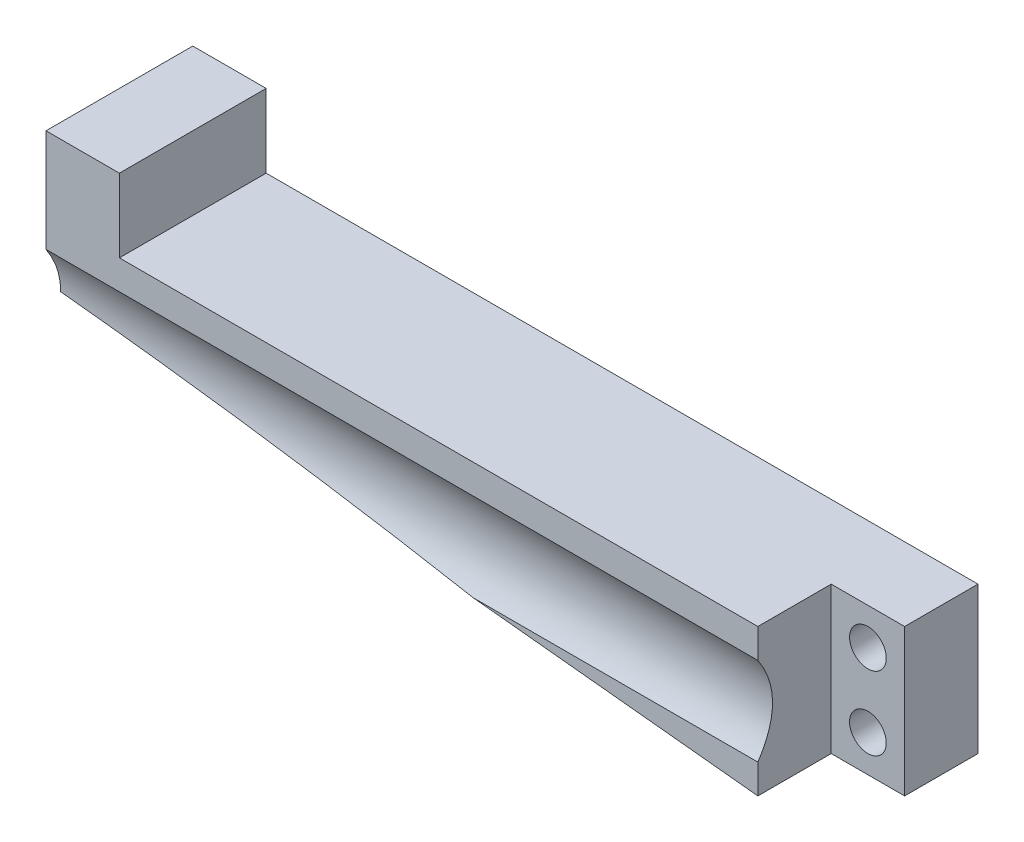
SolidWorks part; units mm, degrees
ref_plane "Plan de face" through (0, 0, 0) normal (0, 0, 1) x (1, 0, 0)
ref_plane "Plan de dessus" through (0, 0, 0) normal (0, 1, 0) x (1, 0, 0)
ref_plane "Plan de droite" through (0, 0, 0) normal (1, 0, 0) x (0, 0, -1)
sketch "Esquisse1" plane through (0, 0, 0) normal (0, 0, 1) x (1, 0, 0)
  line L0 (-102, 0) -> (-5, -10)
  line L1 (-5, -10) -> (5, -10)
  line L3 (-5, 10) -> (5, 10)
  line L4 (5, -10) -> (5, 10)
  line L5 (-5, -10) -> (5, 10) construction
  line L6 (-5, 10) -> (5, -10) construction
  line L7 (-5, 10) -> (-92, 10)
  line L10 (-102, 10) -> (-102, 0)
  line L12 (-102, 10) -> (-102, 20)
  line L13 (-102, 20) -> (-92, 20)
  line L14 (-92, 10) -> (-92, 20)
  circle A0 centre (0, 5) radius 2.5
  circle A1 centre (0, -5) radius 2.5
  point P0 (0, 0)
  dimension "D2" = 5
  dimension "D6" = 5
  dimension "D1" = 20
  dimension "D3" = 10
  dimension "D4" = 5
  dimension "D5" = 5
  dimension "D7" = 97
  dimension "D8" = 10
  dimension "D9" = 10
  dimension "D10" = 10
extrude "Boss.-Extru.1" add sketch "Esquisse1" along normal blind 20
sketch "Esquisse2" plane through (0, 0, 20) normal (0, 0, 1) x (1, 0, 0)
  line L1 (-5, -10) -> (5, -10)
  line L2 (-5, -10) -> (-5, 10)
  line L3 (-5, 10) -> (5, 10)
  line L4 (5, -10) -> (5, 10)
extrude "Enlèv. mat.-Extru.1" cut sketch "Esquisse2" against normal blind 10
sketch "Esquisse4" plane through (-102, 0, 0) normal (-1, 0, 0) x (0, 0, 1)
  line L0 (20, 0) -> (0, 0) construction
  line L1 (20, 20) -> (20, 0) construction
  line L2 (20, 6) -> (20, -6)
  spline S0 degree 2 poles (20, 6) (16, 0) (20, -6) knots 0 0 0 1 1 1
  point P0 (18, 0)
  point P1 (20, 6)
  point P5 (20, -6)
  dimension "D1" = 2
  dimension "D2" = 6
extrude "Enlèv. mat.-Extru.2" cut sketch "Esquisse4" against normal up to surface (97 mm away) up to face at (-5, 0, 15)
